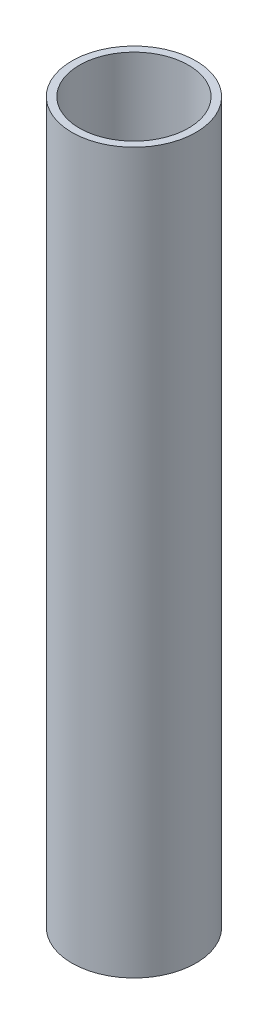
SolidWorks part; units mm, degrees
material "Thornel Mat VMA"
ref_plane "前视基准面" through (0, 0, 0) normal (0, 0, 1) x (1, 0, 0)
ref_plane "上视基准面" through (0, 0, 0) normal (0, 1, 0) x (1, 0, 0)
ref_plane "右视基准面" through (0, 0, 0) normal (1, 0, 0) x (0, 0, -1)
sketch "草图1" plane through (0, 0, 0) normal (0, 1, 0) x (1, 0, 0)
  circle A0 centre (0, 0) radius 11
  circle A1 centre (0, 0) radius 12.5
  dimension "D1" = 25
  dimension "D2" = 22
extrude "凸台-拉伸1" add sketch "草图1" along normal blind 145
